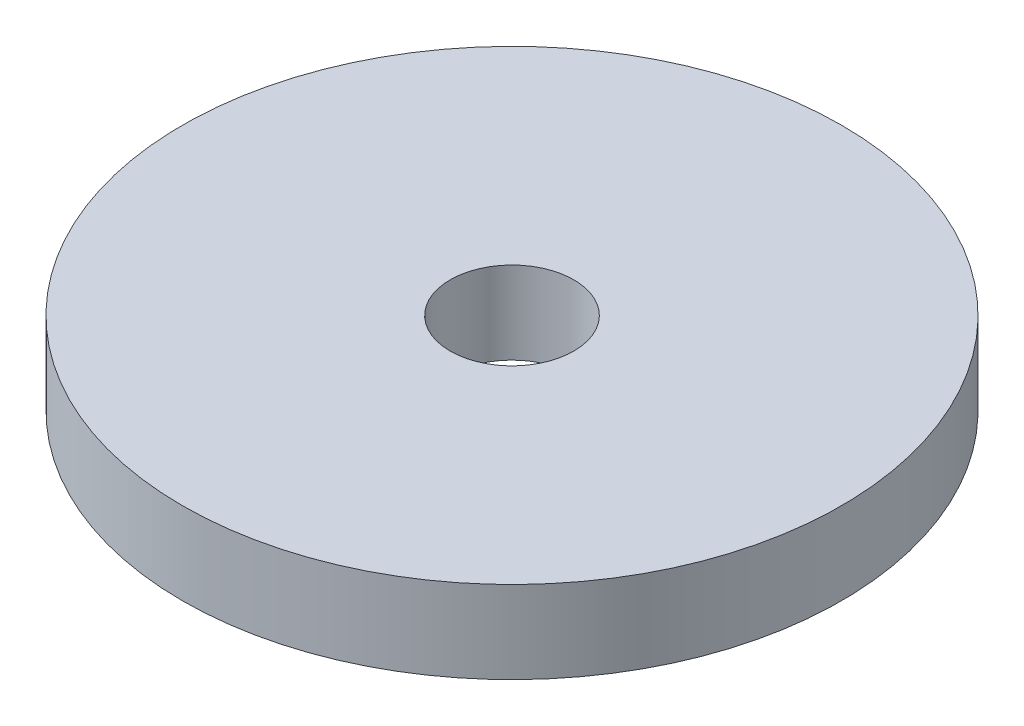
SolidWorks part; units mm, degrees
ref_plane "Front Plane" through (0, 0, 0) normal (0, 0, 1) x (1, 0, 0)
ref_plane "Top Plane" through (0, 0, 0) normal (0, 1, 0) x (1, 0, 0)
ref_plane "Right Plane" through (0, 0, 0) normal (1, 0, 0) x (0, 0, -1)
sketch "Sketch1" plane through (0, 0, 0) normal (0, 1, 0) x (1, 0, 0)
  circle A0 centre (0, 0) radius 12.7
  circle A1 centre (0, 0) radius 2.3813
  dimension "D1" = 25.4
  dimension "D2" = 4.7625
extrude "Boss-Extrude1" add sketch "Sketch1" along normal blind 3.175
